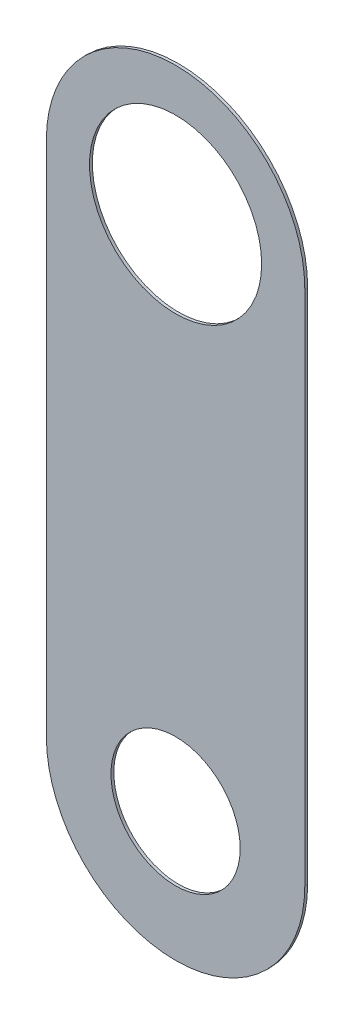
SolidWorks part; units mm, degrees
material "6061-T6 (SS)"
ref_plane "Front Plane" through (0, 0, 0) normal (0, 0, 1) x (1, 0, 0)
ref_plane "Top Plane" through (0, 0, 0) normal (0, 1, 0) x (1, 0, 0)
ref_plane "Right Plane" through (0, 0, 0) normal (1, 0, 0) x (0, 0, -1)
sketch "Sketch1" plane through (0, 0, 0) normal (0, 0, 1) x (1, 0, 0)
  line L0 (0, 0) -> (0, 101.6)
  line L2 (50.8, 101.6) -> (50.8, 0)
  arc A2 (50.8, 101.6) -> (0, 101.6) centre (25.4, 101.6) ccw
  arc A3 (50.8, 0) -> (0, 0) centre (25.4, 0) cw
  dimension "D1" = 101.6
  dimension "D2" = 50.8
extrude "Boss-Extrude1" add sketch "Sketch1" along normal blind 0.5588
sketch "Sketch2" plane through (0, 0, 0.5588) normal (0, 0, 1) x (1, 0, 0)
  line L0 (0, 101.6) -> (0, 0) construction
  line L1 (50.8, 0) -> (50.8, 101.6) construction
  circle A3 centre (25.4, 101.6) radius 16.9164
  circle A4 centre (25.4, 0) radius 12.7
  dimension "D1" = 25.4
  dimension "D2" = 33.8328
  dimension "D3" = 101.6
  dimension "D4" = 50.8
extrude "Cut-Extrude1" cut sketch "Sketch2" against normal through all
